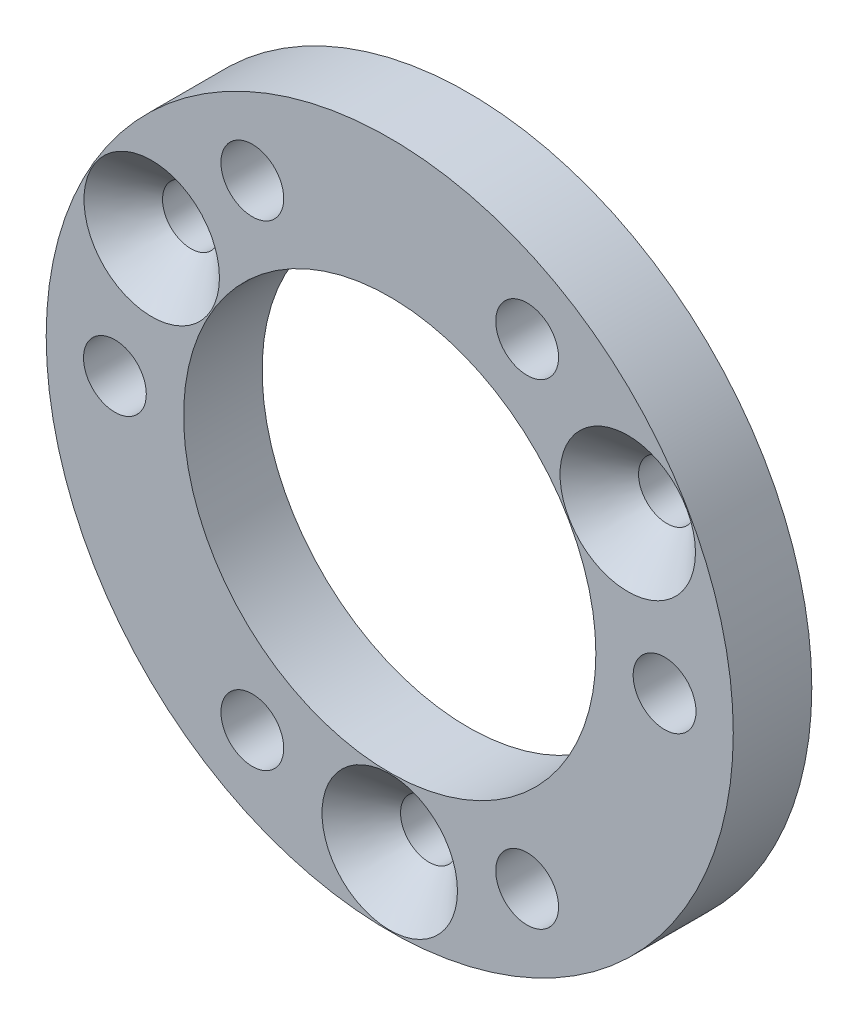
SolidWorks part; units mm, degrees
ref_plane "Front Plane" through (0, 0, 0) normal (0, 0, 1) x (1, 0, 0)
ref_plane "Top Plane" through (0, 0, 0) normal (0, 1, 0) x (1, 0, 0)
ref_plane "Right Plane" through (0, 0, 0) normal (1, 0, 0) x (0, 0, -1)
sketch "Sketch1" plane through (0, 0, 0) normal (0, 0, 1) x (1, 0, 0)
  circle A0 centre (0, 0) radius 17.5
  dimension "D1" = 35
extrude "Boss-Extrude1" add sketch "Sketch1" along normal blind 4
sketch "Sketch2" plane through (0, 0, 4) normal (0, 0, 1) x (1, 0, 0)
  circle A0 centre (0, 0) radius 10.5
  dimension "D1" = 21
extrude "Cut-Extrude1" cut sketch "Sketch2" against normal through all
sketch "Sketch3" plane through (0, 0, 4) normal (0, 0, 1) x (1, 0, 0)
  line L0 (0, 0) -> (20.6195, 0) construction
  circle A0 centre (0, 0) radius 14 construction
  circle A1 centre (14, 0) radius 1.6
  circle A2 centre (7, -12.1244) radius 1.6
  circle A3 centre (-7, -12.1244) radius 1.6
  circle A4 centre (-14, 0) radius 1.6
  circle A5 centre (-7, 12.1244) radius 1.6
  circle A6 centre (7, 12.1244) radius 1.6
  point P19 (0, 0)
  dimension "D1" = 28
  dimension "D2" = 3.2
  dimension "D3" = 6
extrude "Cut-Extrude2" cut sketch "Sketch3" against normal through all
sketch "Sketch4" plane through (0, 0, 4) normal (0, 0, 1) x (1, 0, 0)
  line L0 (0, 0) -> (22.7469, 0) construction
  line L1 (0, 0) -> (19.5292, 11.2752) construction
  circle A0 centre (0, 0) radius 14 construction
  circle A1 centre (12.1244, 7) radius 1.45
  circle A2 centre (0, -14) radius 1.45
  circle A3 centre (-12.1244, 7) radius 1.45
  point P5 (12.1244, 7)
  point P15 (0, 0)
  dimension "D1" = 2.9
  dimension "D2" = 3
extrude "Cut-Extrude3" cut sketch "Sketch4" against normal through all
chamfer "Chamfer1" distance 2 angle 45 3 edges at (-10.6744, 7, 4) (1.45, -14, 4) (13.5744, 7, 4)
